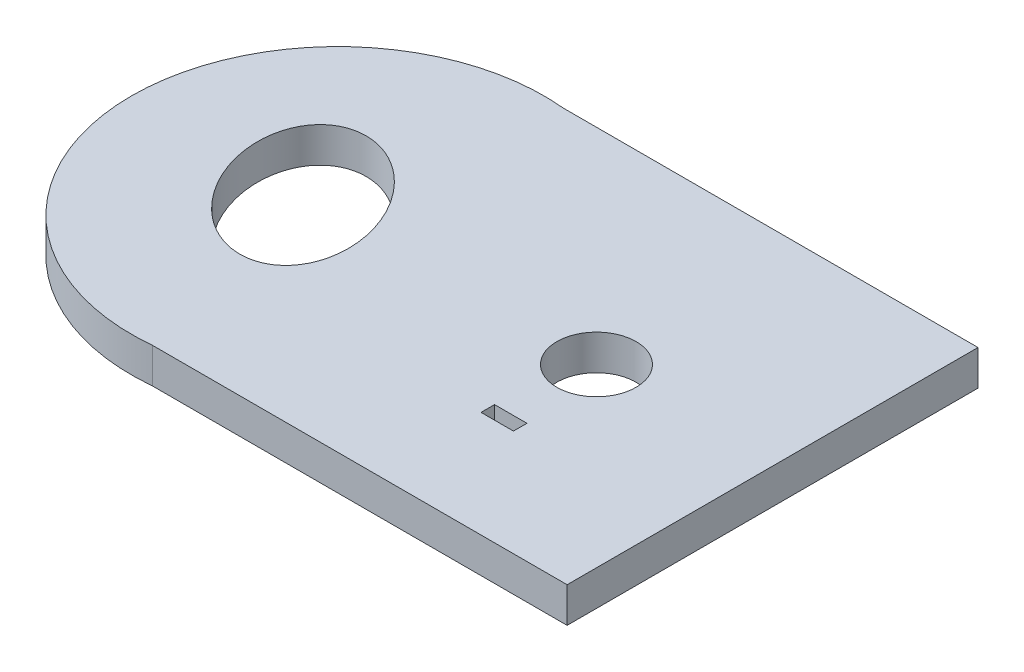
SolidWorks part; units mm, degrees
ref_plane "Front Plane" through (0, 0, 0) normal (0, 0, 1) x (1, 0, 0)
ref_plane "Top Plane" through (0, 0, 0) normal (0, 1, 0) x (1, 0, 0)
ref_plane "Right Plane" through (0, 0, 0) normal (1, 0, 0) x (0, 0, -1)
sketch "Sketch1" plane through (0, 0, 0) normal (0, 1, 0) x (1, 0, 0)
  line L0 (0, 0) -> (0, -35)
  line L1 (0, 0) -> (35.3326, 0)
  line L2 (0, -35) -> (35.3326, -35)
  line L3 (35.3326, 0) -> (35.3326, -35)
  line L4 (17.6663, 0) -> (17.6663, -35) construction
  line L5 (-19.2846, -17.5) -> (35.3326, -17.5) construction
  line L6 (18.9526, -24.8031) -> (21.7126, -24.8031)
  line L7 (18.9526, -24.8031) -> (18.9526, -25.9531)
  line L8 (18.9526, -25.9531) -> (21.7126, -25.9531)
  line L9 (21.7126, -24.8031) -> (21.7126, -25.9531)
  arc A0 (0, 0) -> (0, -35) centre (-1.702, -17.5) ccw
  circle A1 centre (20.3326, -17.5) radius 3.375
  ellipse E0 centre (-4.6674, -17.5) end of major axis (-8.261, -10.917) minor radius 5.3
  dimension "D2" = 6.75
  dimension "D1" = 25
  dimension "D3" = 35
  dimension "D5" = 15
  dimension "D6" = 35.3326
extrude "Boss-Extrude1" add sketch "Sketch1" along normal blind 3
